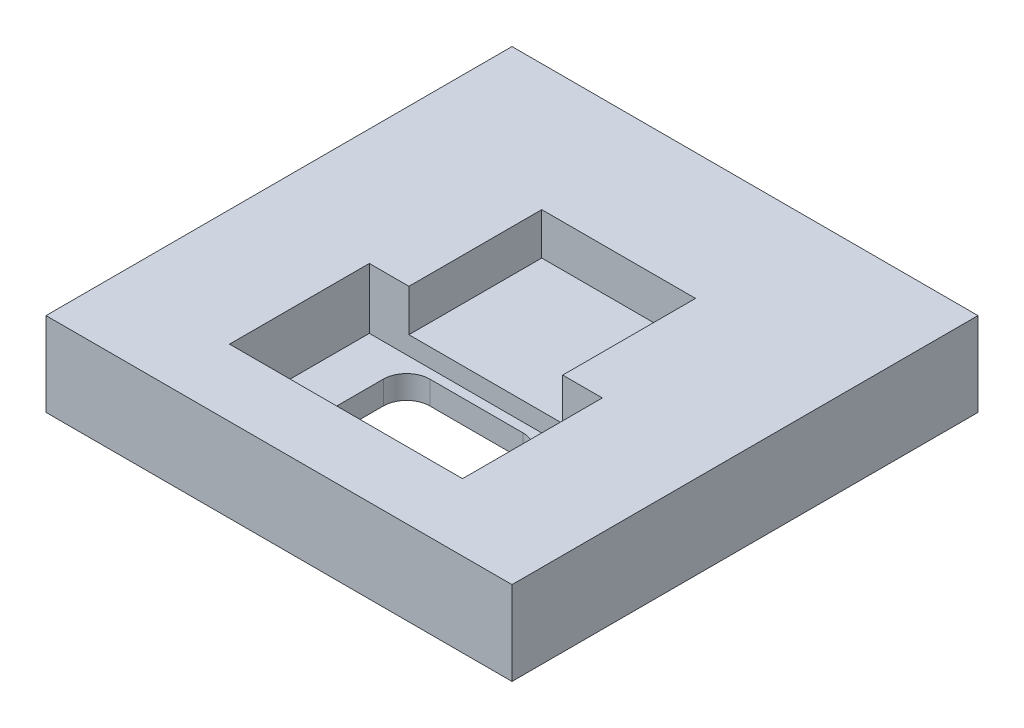
SolidWorks part; units mm, degrees
ref_plane "Спереди" through (0, 0, 0) normal (0, 0, 1) x (1, 0, 0)
ref_plane "Сверху" through (0, 0, 0) normal (0, 1, 0) x (1, 0, 0)
ref_plane "Справа" through (0, 0, 0) normal (1, 0, 0) x (0, 0, -1)
sketch "Эскиз1" plane through (0, 0, 0) normal (0, 1, 0) x (1, 0, 0)
  line L1 (50, -50) -> (-50, -50)
  line L2 (50, -50) -> (50, 50)
  line L3 (50, 50) -> (-50, 50)
  line L4 (-50, -50) -> (-50, 50)
  line L5 (50, -50) -> (-50, 50) construction
  line L6 (50, 50) -> (-50, -50) construction
  point P0 (0, 0)
  dimension "D1" = 100
extrude "Бобышка-Вытянуть1" add sketch "Эскиз1" along normal blind 18
sketch "Эскиз2" plane through (0, 18, 0) normal (0, 1, 0) x (1, 0, 0)
  line L1 (25, -5.6166) -> (-25, -5.6166)
  line L2 (25, -5.6166) -> (25, -35.6166)
  line L3 (25, -35.6166) -> (-25, -35.6166)
  line L4 (-25, -5.6166) -> (-25, -35.6166)
  line L5 (25, -5.6166) -> (-25, -35.6166) construction
  line L6 (25, -35.6166) -> (-25, -5.6166) construction
  point P0 (0, -20.6166)
  point P5 (0, 0)
  dimension "D1" = 50
  dimension "D2" = 30
extrude "Вырез-Вытянуть1" cut sketch "Эскиз2" against normal blind 13
sketch "Эскиз3" plane through (0, 5, 0) normal (0, 1, 0) x (1, 0, 0)
  line L0 (-25, -5.6166) -> (25, -35.6166) construction
  line L1 (0, -20.6166) -> (0, -19.3666) construction
  line L2 (25, -5.6166) -> (-25, -5.6166) construction
  line L3 (10, -31.1166) -> (-10, -31.1166)
  line L4 (15, -26.1166) -> (15, -12.6166)
  line L5 (10, -7.6166) -> (-10, -7.6166)
  line L6 (-15, -26.1166) -> (-15, -12.6166)
  line L7 (15, -31.1166) -> (-15, -7.6166) construction
  line L8 (15, -7.6166) -> (-15, -31.1166) construction
  line L10 (-25, -35.6166) -> (25, -35.6166) construction
  arc A0 (-10, -7.6166) -> (-15, -12.6166) centre (-10, -12.6166) ccw
  arc A1 (-15, -26.1166) -> (-10, -31.1166) centre (-10, -26.1166) ccw
  arc A2 (10, -31.1166) -> (15, -26.1166) centre (10, -26.1166) ccw
  arc A3 (15, -12.6166) -> (10, -7.6166) centre (10, -12.6166) ccw
  point P4 (0, -20.6166)
  point P12 (0, -17.6563)
  dimension "D3" = 5
  dimension "D1" = 30
  dimension "D2" = 23.5
  dimension "D4" = 2
  dimension "D5" = 4.5
extrude "Вырез-Вытянуть2" cut sketch "Эскиз3" against normal through all both and the other way through all
sketch "Эскиз4" plane through (0, 18, 0) normal (0, 1, 0) x (1, 0, 0)
  line L0 (25, -5.6166) -> (-25, -5.6166) construction
  line L1 (16.5, 22.8834) -> (-16.5, 22.8834)
  line L2 (16.5, 22.8834) -> (16.5, -5.6166)
  line L3 (16.5, -5.6166) -> (-16.5, -5.6166)
  line L4 (-16.5, 22.8834) -> (-16.5, -5.6166)
  line L5 (16.5, 22.8834) -> (-16.5, -5.6166) construction
  line L6 (16.5, -5.6166) -> (-16.5, 22.8834) construction
  point P0 (0, 8.6334)
  point P7 (0, 0)
  dimension "D1" = 28.5
  dimension "D2" = 33
extrude "Вырез-Вытянуть3" cut sketch "Эскиз4" against normal blind 9
